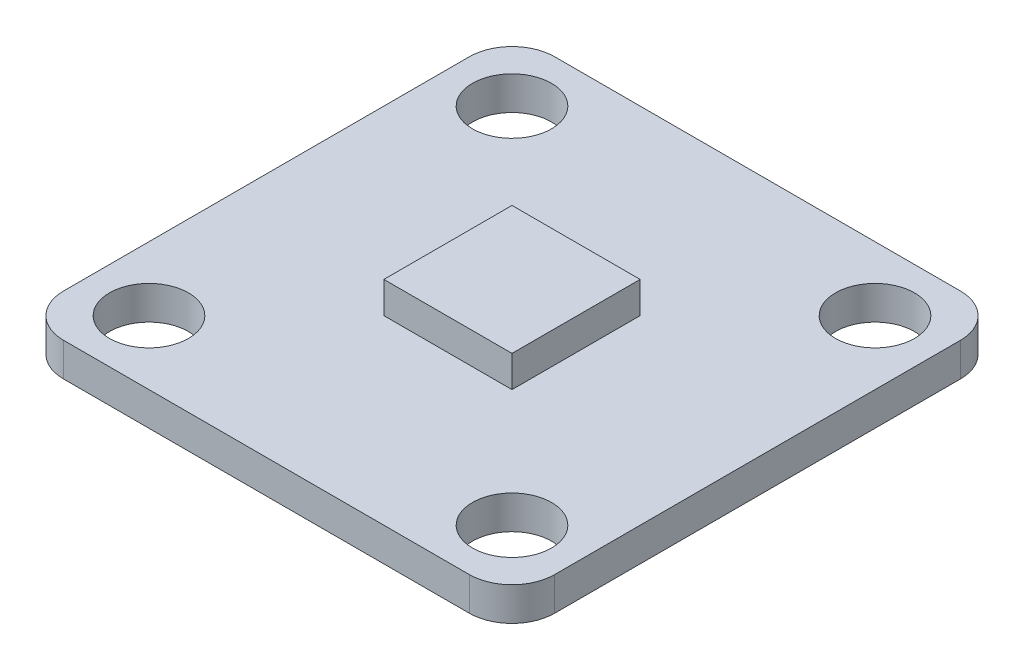
SolidWorks part; units mm, degrees
ref_plane "Front Plane" through (0, 0, 0) normal (0, 0, 1) x (1, 0, 0)
ref_plane "Top Plane" through (0, 0, 0) normal (0, 1, 0) x (1, 0, 0)
ref_plane "Right Plane" through (0, 0, 0) normal (1, 0, 0) x (0, 0, -1)
sketch "Sketch1" plane through (0, 0, 0) normal (0, 1, 0) x (1, 0, 0)
  line L1 (-9.5, -11.5) -> (9.5, -11.5)
  line L2 (-11.5, -9.5) -> (-11.5, 9.5)
  line L3 (-9.5, 11.5) -> (9.5, 11.5)
  line L4 (11.5, -9.5) -> (11.5, 9.5)
  line L5 (-11.5, -11.5) -> (11.5, 11.5) construction
  line L6 (-11.5, 11.5) -> (11.5, -11.5) construction
  line L7 (-8.5, -8.5) -> (8.5, -8.5) construction
  line L8 (-8.5, -8.5) -> (-8.5, 8.5) construction
  line L9 (-8.5, 8.5) -> (8.5, 8.5) construction
  line L10 (8.5, -8.5) -> (8.5, 8.5) construction
  line L11 (-8.5, -8.5) -> (8.5, 8.5) construction
  line L12 (-8.5, 8.5) -> (8.5, -8.5) construction
  line L13 (-3, -3) -> (3, -3)
  line L14 (-3, -3) -> (-3, 3)
  line L15 (-3, 3) -> (3, 3)
  line L16 (3, -3) -> (3, 3)
  line L17 (-3, -3) -> (3, 3) construction
  line L18 (-3, 3) -> (3, -3) construction
  arc A0 (-9.5, -11.5) -> (-11.5, -9.5) centre (-9.5, -9.5) cw
  arc A1 (9.5, -11.5) -> (11.5, -9.5) centre (9.5, -9.5) ccw
  arc A2 (9.5, 11.5) -> (11.5, 9.5) centre (9.5, 9.5) cw
  arc A3 (-11.5, 9.5) -> (-9.5, 11.5) centre (-9.5, 9.5) cw
  circle A4 centre (-8.5, 8.5) radius 1.85
  circle A5 centre (8.5, 8.5) radius 1.85
  circle A6 centre (8.5, -8.5) radius 1.85
  circle A7 centre (-8.5, -8.5) radius 1.85
  point P0 (0, 0)
  point P6 (0, 0)
  point P27 (0, 0)
  point P32 (0, 0)
  dimension "D5" = 2
  dimension "D6" = 3.7
  dimension "D1" = 23
  dimension "D2" = 23
  dimension "D3" = 17
  dimension "D4" = 17
  dimension "D7" = 6
  dimension "D8" = 6
extrude "Boss-Extrude1" add sketch "Sketch1" along normal blind 1.57 contours L13 L16 L15 L14 | A3 L2 A0 L1 A1 L4 A2 L3 A7 A6 A5 A4 L16 L13 L14 L15
sketch "Sketch2" plane through (0, 1.57, 0) normal (0, 1, 0) x (1, 0, 0)
  line L4 (-3, -3) -> (3, -3)
  line L5 (3, -3) -> (3, 3)
  line L6 (3, 3) -> (-3, 3)
  line L7 (-3, 3) -> (-3, -3)
  line L8 (-3, -3) -> (3, -3)
  line L9 (3, -3) -> (3, 3)
  line L10 (3, 3) -> (-3, 3)
  line L11 (-3, 3) -> (-3, -3)
  line L12 (-11.5, 9.5) -> (-11.5, -9.5)
  line L13 (-9.5, -11.5) -> (9.5, -11.5)
  line L14 (11.5, -9.5) -> (11.5, 9.5)
  line L15 (9.5, 11.5) -> (-9.5, 11.5)
  line L16 (-11.5, 9.5) -> (-11.5, -9.5)
  line L17 (-9.5, -11.5) -> (9.5, -11.5)
  line L18 (11.5, -9.5) -> (11.5, 9.5)
  line L19 (9.5, 11.5) -> (-9.5, 11.5)
  circle A1 centre (8.5, 8.5) radius 1.85
  circle A2 centre (8.5, 8.5) radius 1.85
  circle A3 centre (-8.5, -8.5) radius 1.85
  circle A4 centre (-8.5, -8.5) radius 1.85
  circle A5 centre (8.5, -8.5) radius 1.85
  circle A6 centre (8.5, -8.5) radius 1.85
  circle A7 centre (-8.5, 8.5) radius 1.85
  circle A8 centre (-8.5, 8.5) radius 1.85
  arc A12 (-11.5, -9.5) -> (-9.5, -11.5) centre (-9.5, -9.5) ccw
  arc A13 (9.5, -11.5) -> (11.5, -9.5) centre (9.5, -9.5) ccw
  arc A14 (11.5, 9.5) -> (9.5, 11.5) centre (9.5, 9.5) ccw
  arc A15 (-9.5, 11.5) -> (-11.5, 9.5) centre (-9.5, 9.5) ccw
  arc A16 (-11.5, -9.5) -> (-9.5, -11.5) centre (-9.5, -9.5) ccw
  arc A17 (9.5, -11.5) -> (11.5, -9.5) centre (9.5, -9.5) ccw
  arc A18 (11.5, 9.5) -> (9.5, 11.5) centre (9.5, 9.5) ccw
  arc A19 (-9.5, 11.5) -> (-11.5, 9.5) centre (-9.5, 9.5) ccw
  dimension "D1" = 0
  dimension "D2" = 0
  dimension "D3" = 0
  dimension "D4" = 0
  dimension "D5" = 0
  dimension "D6" = 0
extrude "Boss-Extrude2" add sketch "Sketch2" along normal blind 1.47 contours L10 L11 L8 L9
equation "\"a\"= 1"
equation "\"b\"= 1"
equation "\"c\"= 1"
equation "\"d\"= 1"
equation "\"e\"= 1"
equation "\"x\"= 1"
equation "\"y\"= 1"
equation "\"z\"= 1"
